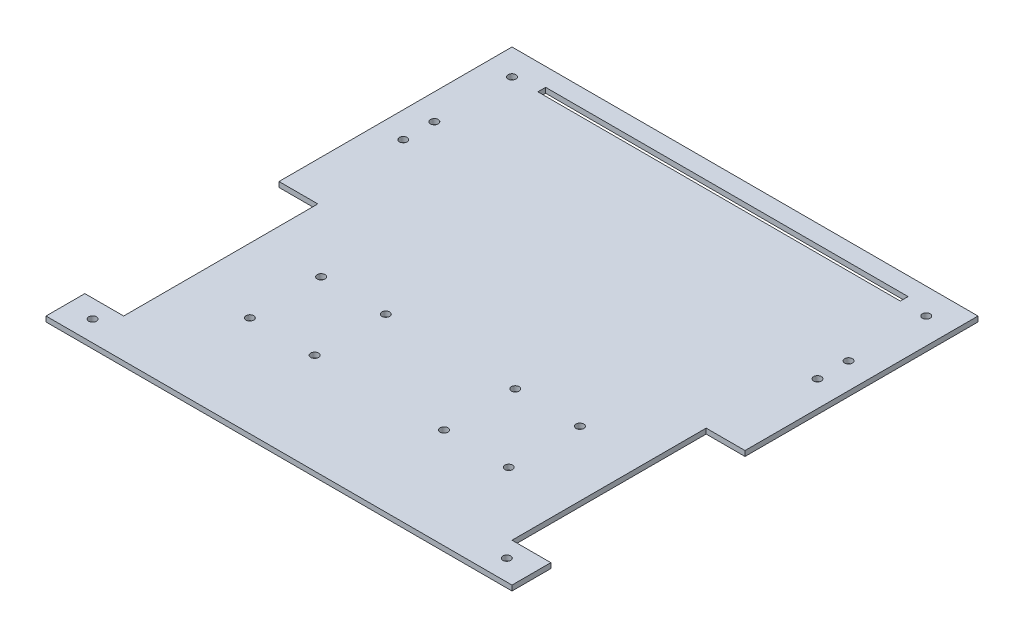
SolidWorks part; units mm, degrees
ref_plane "Front Plane" through (0, 0, 0) normal (0, 0, 1) x (1, 0, 0)
ref_plane "Top Plane" through (0, 0, 0) normal (0, 1, 0) x (1, 0, 0)
ref_plane "Right Plane" through (0, 0, 0) normal (1, 0, 0) x (0, 0, -1)
sketch "Sketch1" plane through (0, 0, 0) normal (0, 1, 0) x (1, 0, 0)
  line L1 (-90, 90) -> (90, 90)
  line L2 (-90, 90) -> (-90, -90)
  line L3 (-90, -90) -> (90, -90)
  line L4 (90, 90) -> (90, -90)
  line L5 (-90, 90) -> (90, -90) construction
  line L6 (-90, -90) -> (90, 90) construction
  point P0 (0, 0)
  dimension "D1" = 180
  dimension "D2" = 180
extrude "Boss-Extrude1" add sketch "Sketch1" along normal blind 2
sketch "Sketch2" plane through (0, 2, 0) normal (0, 1, 0) x (1, 0, 0)
  line L0 (-90, 90) -> (-90, -90) construction
  line L1 (-90, 0) -> (-75, 0)
  line L2 (-90, 0) -> (-90, -75)
  line L3 (-90, -75) -> (-75, -75)
  line L4 (-75, 0) -> (-75, -75)
  line L5 (90, -90) -> (90, 90) construction
  line L10 (0, 0) -> (0, -84.7427) construction
  line L11 (90, -75) -> (75, -75)
  line L12 (90, 0) -> (90, -75)
  line L13 (75, 0) -> (75, -75)
  line L14 (90, 0) -> (75, 0)
  line L15 (-90, -90) -> (90, -90) construction
  line L16 (90, 90) -> (-90, 90) construction
  line L18 (-70, 83) -> (70, 83)
  line L19 (-70, 83) -> (-70, 80)
  line L20 (-70, 80) -> (70, 80)
  line L21 (70, 83) -> (70, 80)
  circle A0 centre (-80, 38) radius 1.5
  circle A1 centre (-80, -82) radius 1.5
  circle A2 centre (80, -82) radius 1.5
  circle A3 centre (80, 38) radius 1.5
  circle A4 centre (-80, 80) radius 1.5
  circle A5 centre (-80, 50) radius 1.5
  circle A6 centre (80, 50) radius 1.5
  circle A7 centre (80, 80) radius 1.5
  point P37 (70, 81.5)
  dimension "D3" = 3
  dimension "D4" = 3
  dimension "D10" = 3
  dimension "D11" = 3
  dimension "D1" = 75
  dimension "D2" = 15
  dimension "D5" = 10
  dimension "D6" = 10
  dimension "D7" = 8
  dimension "D8" = 120
  dimension "D9" = 15
  dimension "D12" = 10
  dimension "D13" = 10
  dimension "D14" = 10
  dimension "D15" = 30
  dimension "D16" = 3
  dimension "D17" = 140
  dimension "D18" = 20
extrude "Cut-Extrude1" cut sketch "Sketch2" against normal blind 2
sketch "Sketch3" plane through (0, 2, 0) normal (0, 1, 0) x (1, 0, 0)
  line L0 (-75, 0) -> (-90, 0) construction
  line L1 (-90, -75) -> (-75, -75) construction
  line L2 (-75, -75) -> (-75, 0) construction
  line L3 (75, 0) -> (75, -75) construction
  circle A0 centre (-50, -23.75) radius 1.5
  circle A1 centre (-50, -51.25) radius 1.5
  circle A2 centre (-25, -23.75) radius 1.5
  circle A3 centre (-25, -51.25) radius 1.5
  circle A4 centre (25, -23.75) radius 1.5
  circle A5 centre (50, -23.75) radius 1.5
  circle A6 centre (25, -51.25) radius 1.5
  circle A7 centre (50, -51.25) radius 1.5
  point P16 (0, 0)
  point P17 (0, 0)
  point P18 (0, 0)
  point P19 (0, 0)
  dimension "D1" = 3
  dimension "D2" = 3
  dimension "D3" = 3
  dimension "D4" = 3
  dimension "D5" = 3
  dimension "D6" = 3
  dimension "D7" = 3
  dimension "D8" = 3
  dimension "D9" = 23.75
  dimension "D10" = 23.75
  dimension "D11" = 25
  dimension "D12" = 25
  dimension "D13" = 25
  dimension "D14" = 25
extrude "Cut-Extrude2" cut sketch "Sketch3" against normal blind 3
